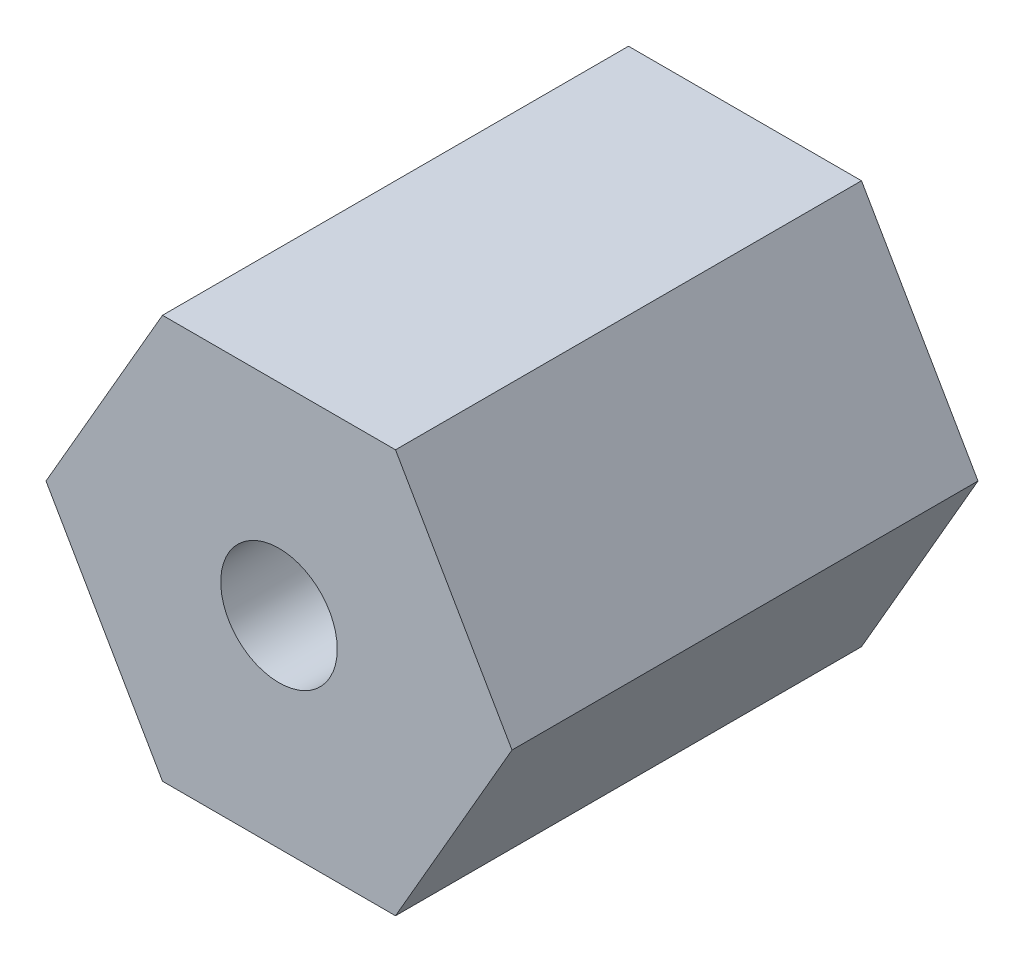
SolidWorks part; units mm, degrees
ref_plane "Front" through (0, 0, 0) normal (0, 0, 1) x (1, 0, 0)
ref_plane "Top" through (0, 0, 0) normal (0, 1, 0) x (1, 0, 0)
ref_plane "Right" through (0, 0, 0) normal (1, 0, 0) x (0, 0, -1)
sketch "Sketch1" plane through (0, 0, 0) normal (0, 0, 1) x (1, 0, 0)
  line L1 (12, 0) -> (6, 10.3923)
  line L2 (6, 10.3923) -> (-6, 10.3923)
  line L3 (-6, 10.3923) -> (-12, 0)
  line L4 (-12, 0) -> (-6, -10.3923)
  line L5 (-6, -10.3923) -> (6, -10.3923)
  line L6 (6, -10.3923) -> (12, 0)
  circle A2 centre (0, 0) radius 10.3923 construction
  dimension "D1" = 12
extrude "Boss-Extrude1" add sketch "Sketch1" along normal blind 12
sketch "Sketch3" plane through (0, 0, 12) normal (0, 0, 1) x (1, 0, 0)
  circle A0 centre (0, 0) radius 3
  dimension "D1" = 6
extrude "Cut-Extrude1" cut sketch "Sketch3" against normal blind 5
sketch "Sketch4" plane through (0, 0, 0) normal (0, 0, -1) x (-1, 0, 0)
  line L1 (12, 0) -> (6, 10.3923)
  line L2 (6, 10.3923) -> (-6, 10.3923)
  line L3 (-6, 10.3923) -> (-12, 0)
  line L4 (-12, 0) -> (-6, -10.3923)
  line L5 (-6, -10.3923) -> (6, -10.3923)
  line L6 (6, -10.3923) -> (12, 0)
  circle A0 centre (0, 0) radius 10.3923 construction
extrude "Boss-Extrude2" add sketch "Sketch4" along normal blind 12
sketch "Sketch5" plane through (0, 0, -12) normal (0, 0, -1) x (-1, 0, 0)
  circle A0 centre (0, 0) radius 2
  dimension "D1" = 4
extrude "Cut-Extrude2" cut sketch "Sketch5" against normal blind 5
